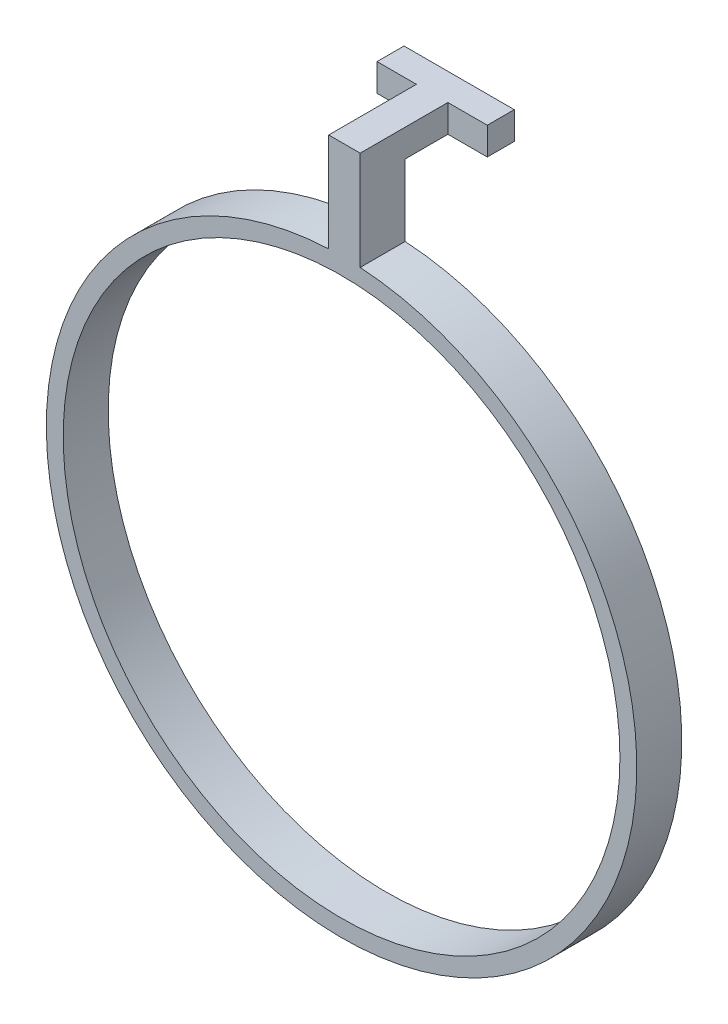
SolidWorks part; units mm, degrees
ref_plane "Front Plane" through (0, 0, 0) normal (0, 0, 1) x (1, 0, 0)
ref_plane "Top Plane" through (0, 0, 0) normal (0, 1, 0) x (1, 0, 0)
ref_plane "Right Plane" through (0, 0, 0) normal (1, 0, 0) x (0, 0, -1)
sketch "Sketch2" plane through (0, 0, 0) normal (0, 0, 1) x (1, 0, 0)
  line L0 (0, 0) -> (0, 32.1) construction
  line L2 (-1.1449, 35) -> (1.6551, 35)
  line L3 (-1.1449, 35) -> (-1.1449, 26.225)
  line L5 (1.6551, 35) -> (1.6551, 26.1978)
  line L6 (-1.1449, 35) -> (1.2201, 29.0094) construction
  line L7 (-1.5373, 29.4064) -> (1.6551, 35) construction
  circle A0 centre (0, 0) radius 24.75
  arc A1 (-1.1449, 26.225) -> (1.6551, 26.1978) centre (0, 0) ccw
  dimension "D1" = 49.5
  dimension "D2" = 52.5
  dimension "D3" = 2.8
  dimension "D4" = 35
extrude "Boss-Extrude1" add sketch "Sketch2" along normal blind 4
sketch "Sketch3" plane through (0, 0, 0) normal (0, 0, -1) x (-1, 0, 0)
  line L1 (-1.6551, 35) -> (1.1449, 35)
  line L2 (-1.6551, 35) -> (-1.6551, 32.55)
  line L3 (-1.6551, 32.55) -> (1.1449, 32.55)
  line L4 (1.1449, 35) -> (1.1449, 32.55)
  dimension "D1" = 2.45
  dimension "D2" = 2.8
extrude "Boss-Extrude2" add sketch "Sketch3" along normal blind 3.8
sketch "Sketch4" plane through (1.6551, 0, 0) normal (1, 0, 0) x (0, 0, -1)
  line L1 (3.8, 35) -> (6.2, 35)
  line L2 (3.8, 35) -> (3.8, 32.55)
  line L3 (3.8, 32.55) -> (6.2, 32.55)
  line L4 (6.2, 35) -> (6.2, 32.55)
  dimension "D1" = 2.4
  dimension "D2" = 2.45
extrude "Boss-Extrude3" add sketch "Sketch4" along normal blind 9.8 from offset 6.3 offset against normal yes
